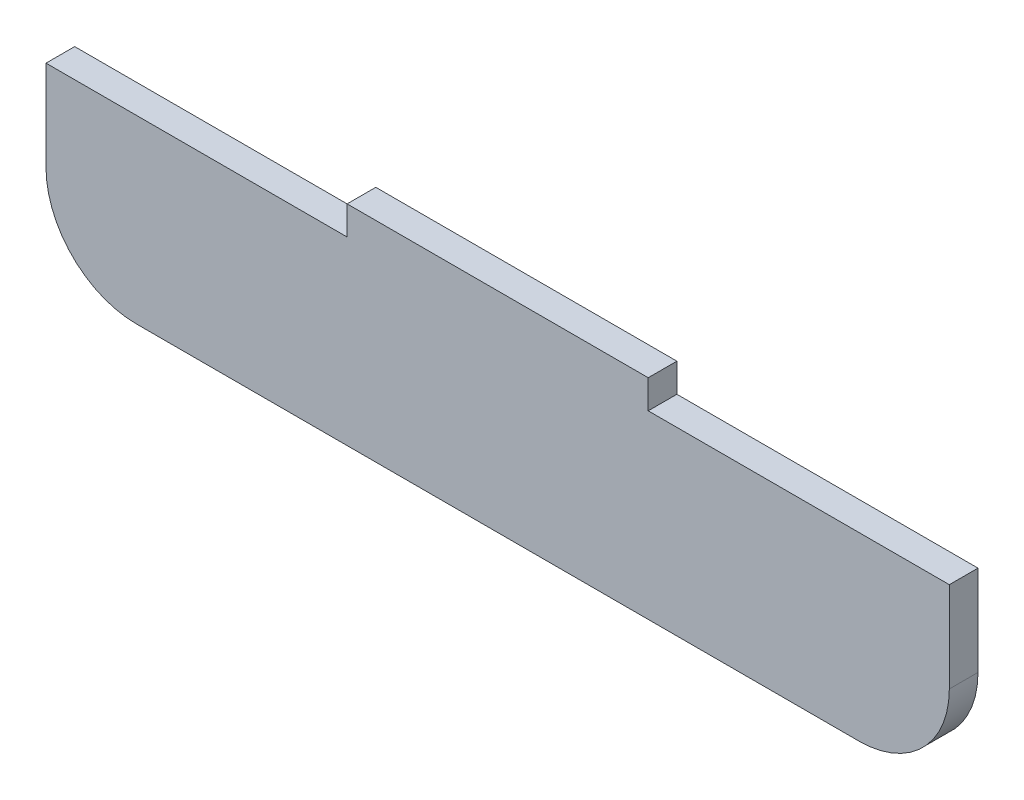
SolidWorks part; units mm, degrees
ref_plane "Front Plane" through (0, 0, 0) normal (0, 0, 1) x (1, 0, 0)
ref_plane "Top Plane" through (0, 0, 0) normal (0, 1, 0) x (1, 0, 0)
ref_plane "Right Plane" through (0, 0, 0) normal (1, 0, 0) x (0, 0, -1)
sketch "Sketch1" plane through (0, 0, 0) normal (0, 0, 1) x (1, 0, 0)
  line L0 (0, 20) -> (33.3333, 20)
  line L1 (0, 0) -> (100, 0)
  line L2 (0, 0) -> (0, 20)
  line L3 (0, 20) -> (100, 20) construction
  line L4 (100, 0) -> (100, 20)
  line L5 (33.3333, 20) -> (33.3333, 23.175)
  line L6 (33.3333, 23.175) -> (66.6667, 23.175)
  line L7 (66.6667, 23.175) -> (66.6667, 20)
  line L8 (66.6667, 20) -> (100, 20)
  dimension "D1" = 100
  dimension "D2" = 20
  dimension "D3" = 3.175
extrude "Boss-Extrude1" add sketch "Sketch1" along normal blind 3.175
fillet "Fillet1" radius 10 2 edges at (0, 0, 1.5875) (100, 0, 1.5875)
